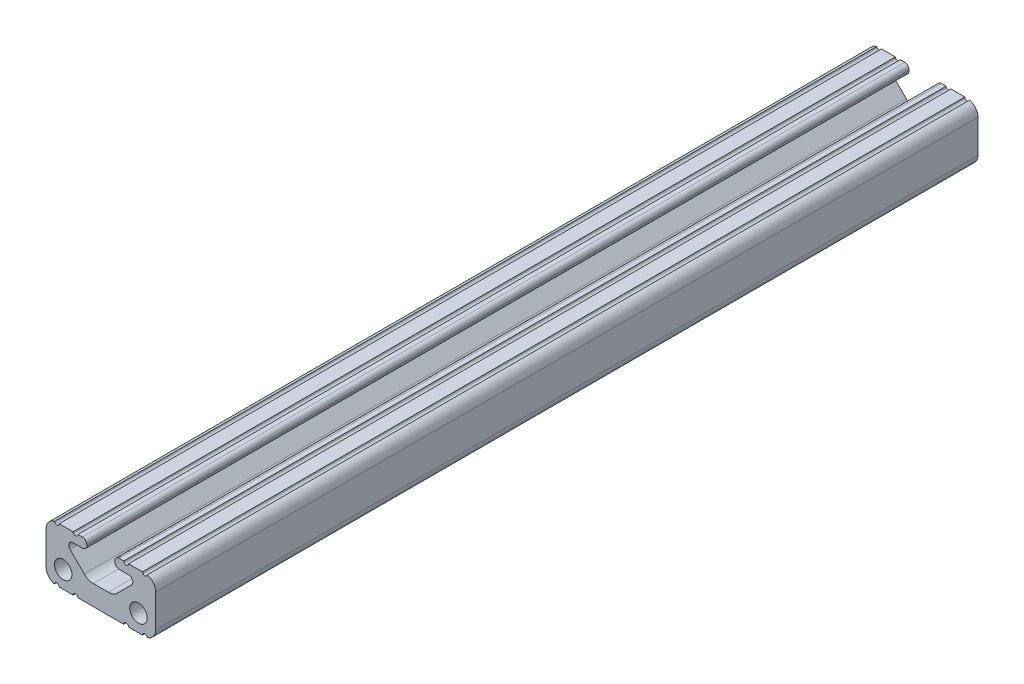
SolidWorks part; units mm, degrees
ref_plane "Front Plane" through (0, 0, 0) normal (0, 0, 1) x (1, 0, 0)
ref_plane "Top Plane" through (0, 0, 0) normal (0, 1, 0) x (1, 0, 0)
ref_plane "Right Plane" through (0, 0, 0) normal (1, 0, 0) x (0, 0, -1)
sketch "Sketch1" plane through (0, 0, 0) normal (0, 0, 1) x (1, 0, 0)
  line L0 (0, 6.35) -> (0, -6.35) construction
  line L1 (0, -6.35) -> (12.7, -6.35)
  line L2 (12.7, -6.35) -> (12.7, 6.35)
  line L3 (12.7, 6.35) -> (3.2512, 6.35)
  line L4 (3.2512, 6.35) -> (3.2512, 4.1402)
  line L5 (3.2512, 4.1402) -> (6.4224, 4.1402)
  line L6 (7.1255, 2.4426) -> (2.9811, -1.7018)
  line L7 (2.9811, -1.7018) -> (0, -1.7018)
  circle A0 centre (8.7249, -2.3876) radius 2.032
  arc A1 (6.4224, 4.1402) -> (7.1255, 2.4426) centre (6.4224, 3.1458) cw
  dimension "Center Hole Diameter" = 4.064
  dimension "D3" = 0.9944
  dimension "Rail Height" = 25.4
  dimension "Rail Width" = 12.7
  dimension "Hole CtoC" = 17.4498
  dimension "D1" = 3.9624
  dimension "T-Slot Width" = 6.5024
  dimension "Thickness" = 2.2098
  dimension "Inner Slot Width" = 14.8336
  dimension "Slot Depth" = 5.842
  dimension "D2" = 45
sketch "Sketch2" plane through (0, 0, 0) normal (1, 0, 0) x (0, 0, -1)
  line L0 (-152.4, -6.35) -> (152.4, -6.35) construction
  line L1 (-127, 0) -> (127, 0) construction
  dimension "Length" = 304.8
  dimension "D1" = 25.4
sketch "Sketch3" plane through (0, 0, 0) normal (0, 0, 1) x (1, 0, 0)
  line L0 (3.2512, 6.35) -> (3.2512, 4.1402) construction
  line L1 (12.7, 6.35) -> (3.2512, 6.35) construction
  line L2 (3.2512, 4.1402) -> (6.4224, 4.1402) construction
  line L3 (3.2512, 5.3556) -> (3.2512, 5.1346)
  line L4 (12.7, -6.35) -> (12.7, 6.35) construction
  line L5 (0, -6.35) -> (12.7, -6.35) construction
  line L6 (2.9811, -1.7018) -> (0, -1.7018) construction
  line L7 (7.1255, 2.4426) -> (2.9811, -1.7018) construction
  line L8 (0, -1.7018) -> (1.7454, -1.7018)
  line L9 (4.2456, 4.1402) -> (6.4224, 4.1402)
  line L10 (3.8549, -0.828) -> (7.1255, 2.4426)
  line L11 (0, -1.7018) -> (0, -6.35)
  line L12 (0, -6.35) -> (10.16, -6.35)
  line L13 (12.7, -3.81) -> (12.7, 3.81)
  line L14 (4.2456, 6.35) -> (10.16, 6.35)
  arc A0 (3.2512, 5.3556) -> (4.2456, 6.35) centre (4.2456, 5.3556) cw
  arc A1 (3.2512, 5.1346) -> (4.2456, 4.1402) centre (4.2456, 5.1346) ccw
  arc A2 (7.1255, 2.4426) -> (6.4224, 4.1402) centre (6.4224, 3.1458) ccw construction
  arc A3 (10.16, 6.35) -> (12.7, 3.81) centre (10.16, 3.81) cw
  arc A4 (10.16, -6.35) -> (12.7, -3.81) centre (10.16, -3.81) ccw
  arc A5 (7.1255, 2.4426) -> (6.4224, 4.1402) centre (6.4224, 3.1458) ccw
  circle A6 centre (8.7249, -2.3876) radius 2.032 construction
  circle A7 centre (8.7249, -2.3876) radius 2.032
  arc A8 (1.7454, -1.7018) -> (3.8549, -0.828) centre (1.7454, 1.2814) ccw
  dimension "D2" = 2.9832
  dimension "D1" = 2.54
extrude "Boss-Extrude1" add sketch "Sketch3" along normal mid plane 304.8
sketch "Sketch4" plane through (0, 0, 0) normal (0, 0, 1) x (1, 0, 0)
  line L0 (12.7, 6.35) -> (3.2512, 6.35) construction
  line L1 (0, -6.35) -> (12.7, -6.35) construction
  line L2 (10.7569, -2.3876) -> (10.7569, 6.35) construction
  line L3 (6.4224, 3.1458) -> (6.4224, 6.35) construction
  circle A0 centre (5.8699, 6.35) radius 0.5524
  circle A1 centre (10.2045, 6.35) radius 0.5524
  circle A2 centre (5.8699, -6.35) radius 0.5524
  circle A3 centre (10.2045, -6.35) radius 0.5524
  circle A4 centre (8.7249, -2.3876) radius 2.032 construction
  dimension "D1" = 1.1049
extrude "Cut-Extrude1" cut sketch "Sketch4" against normal through all both and the other way through all
mirror "Mirror1" about plane through (0, 0, 0) normal (1, 0, 0) of bodies 135
sketch "Sketch5" plane through (0, -6.35, 0) normal (0, -1, 0) x (1, 0, 0)
  line L0 (-5.3175, 152.4) -> (5.3175, 152.4) construction
  line L1 (-25.4, -152.4) -> (25.4, -152.4)
  line L2 (-25.4, -152.4) -> (-25.4, -38.1)
  line L3 (-25.4, -38.1) -> (25.4, -38.1)
  line L4 (25.4, -152.4) -> (25.4, -38.1)
  line L5 (-5.3175, -152.4) -> (5.3175, -152.4) construction
  dimension "D1" = 190.5
  dimension "D2" = 50.8
  dimension "D3" = 25.4
extrude "Cut-Extrude2" cut sketch "Sketch5" against normal through all
equation "\"D3@Sketch1\"=\"Thickness@Sketch1\"*0.45"
equation "\"D1@Sketch3\"=\"Rail Width@Sketch1\"*0.2"
equation "\"D2@Sketch3\"=\"D3@Sketch1\"*3"
equation "\"D1@Boss-Extrude1\"=\"length@sketch2\""
equation "\"D1@Sketch4\"=\"Thickness@Sketch1\"*0.5"
